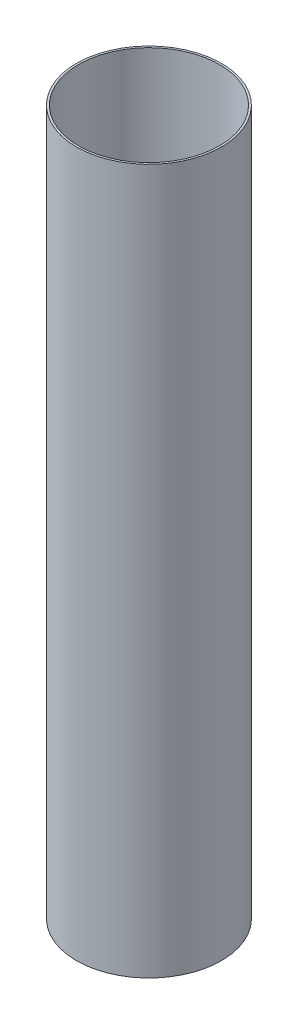
SolidWorks part; units mm, degrees
ref_plane "Front Plane" through (0, 0, 0) normal (0, 0, 1) x (1, 0, 0)
ref_plane "Top Plane" through (0, 0, 0) normal (0, 1, 0) x (1, 0, 0)
ref_plane "Right Plane" through (0, 0, 0) normal (1, 0, 0) x (0, 0, -1)
sketch "Sketch1" plane through (0, 0, 0) normal (0, 1, 0) x (1, 0, 0)
  circle A0 centre (0, 0) radius 76.2
  circle A1 centre (0, 0) radius 78.359
  dimension "D1" = 156.718
  dimension "D2" = 152.4
extrude "Boss-Extrude1" add sketch "Sketch1" along normal blind 762
equation "\"Length\"= 30in"
equation "\"D1@Boss-Extrude1\"=\"Length\""
